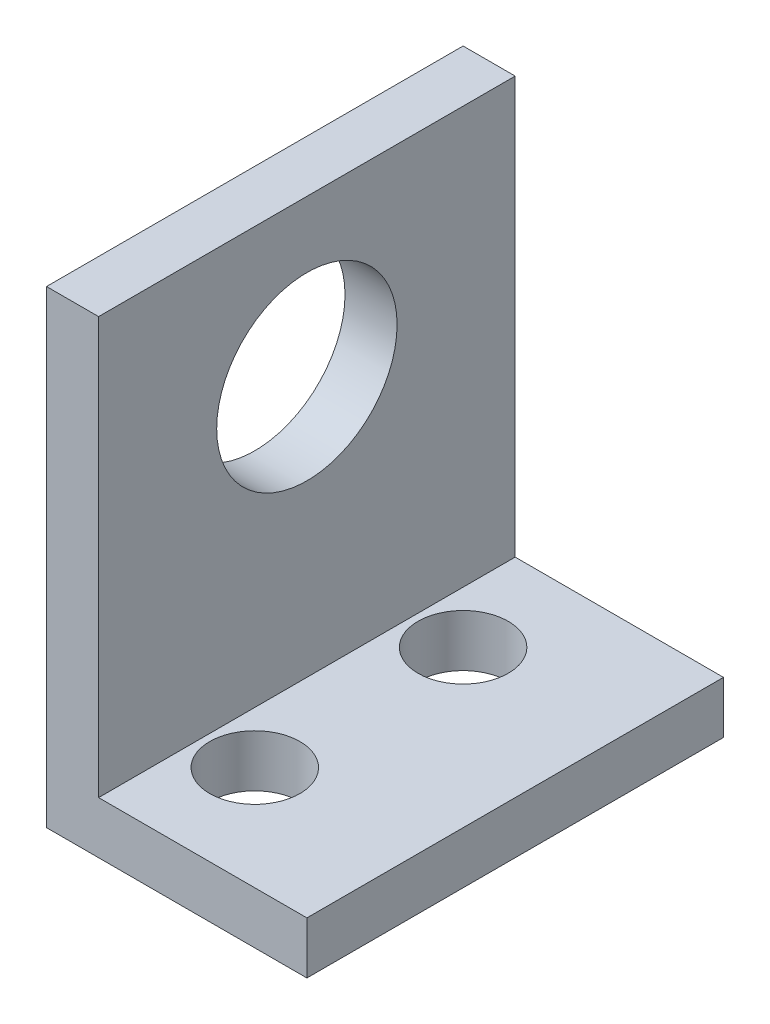
SolidWorks part; units mm, degrees
material "6061 Alloy"
ref_plane "Front Plane" through (0, 0, 0) normal (0, 0, 1) x (1, 0, 0)
ref_plane "Top Plane" through (0, 0, 0) normal (0, 1, 0) x (1, 0, 0)
ref_plane "Right Plane" through (0, 0, 0) normal (1, 0, 0) x (0, 0, -1)
sketch "Sketch1" plane through (0, 0, 0) normal (0, 0, 1) x (1, 0, 0)
  line L0 (0, 0) -> (15.875, 0)
  line L1 (15.875, 0) -> (15.875, 3.175)
  line L2 (15.875, 3.175) -> (3.175, 3.175)
  line L3 (3.175, 3.175) -> (3.175, 28.575)
  line L4 (3.175, 28.575) -> (0, 28.575)
  line L5 (0, 28.575) -> (0, 0)
  dimension "D1" = 3.175
  dimension "D2" = 3.175
  dimension "D3" = 25.4
  dimension "D4" = 12.7
extrude "Boss-Extrude1" add sketch "Sketch1" along normal blind 25.4
sketch "Sketch2" plane through (3.175, 0, 0) normal (1, 0, 0) x (0, 0, -1)
  line L0 (0, 3.175) -> (0, 28.575) construction
  line L1 (-25.4, 28.575) -> (0, 28.575) construction
  point P0 (-12.7, 19.05)
  dimension "D1" = 12.7
  dimension "D2" = 9.525
hole_wizard "M10 Clearance Hole1" positions "Sketch3" profile "Sketch4" hole size "M10" standard "ANSI Metric" end condition through all
sketch "Sketch3" plane through (3.175, 0, 0) normal (1, 0, 0) x (0, 0, -1)
  point P0 (-12.7, 19.05)
sketch "Sketch4" plane through (3.175, 19.05, 12.7) normal (0, 1, 0) x (0, 0, -1)
  line L0 (0, 0) -> (0, 3.175)
  line L1 (0, 3.175) -> (5.5, 3.175)
  line L2 (5.5, 3.175) -> (5.5, 0)
  line L5 (5.5, 0) -> (0, 0)
  line L11 (0, -6.35) -> (0, 107.95) construction
  dimension "Thru Hole Dia." = 11
  dimension "Thru Hole Depth" = 3.175
sketch "Sketch5" plane through (0, 3.175, 0) normal (0, 1, 0) x (1, 0, 0)
  line L0 (15.875, -25.4) -> (15.875, 0) construction
  line L1 (15.875, 0) -> (3.175, 0) construction
  point P0 (6.35, -19.05)
  point P5 (6.35, -6.35)
  dimension "D1" = 9.525
  dimension "D2" = 19.05
  dimension "D3" = 6.35
hole_wizard "M5 Clearance Hole2" positions "Sketch6" profile "Sketch7" hole size "M5" standard "ANSI Metric" end condition through all
sketch "Sketch6" plane through (0, 3.175, 0) normal (0, 1, 0) x (1, 0, 0)
  point P0 (6.35, -19.05)
  point P3 (6.35, -6.35)
sketch "Sketch7" plane through (6.35, 3.175, 19.05) normal (1, 0, 0) x (0, 0, 1)
  line L0 (0, 0) -> (0, 3.175)
  line L1 (0, 3.175) -> (2.75, 3.175)
  line L2 (2.75, 3.175) -> (2.75, 0)
  line L5 (2.75, 0) -> (0, 0)
  line L11 (0, -6.35) -> (0, 107.95) construction
  dimension "Thru Hole Dia." = 5.5
  dimension "Thru Hole Depth" = 3.175
